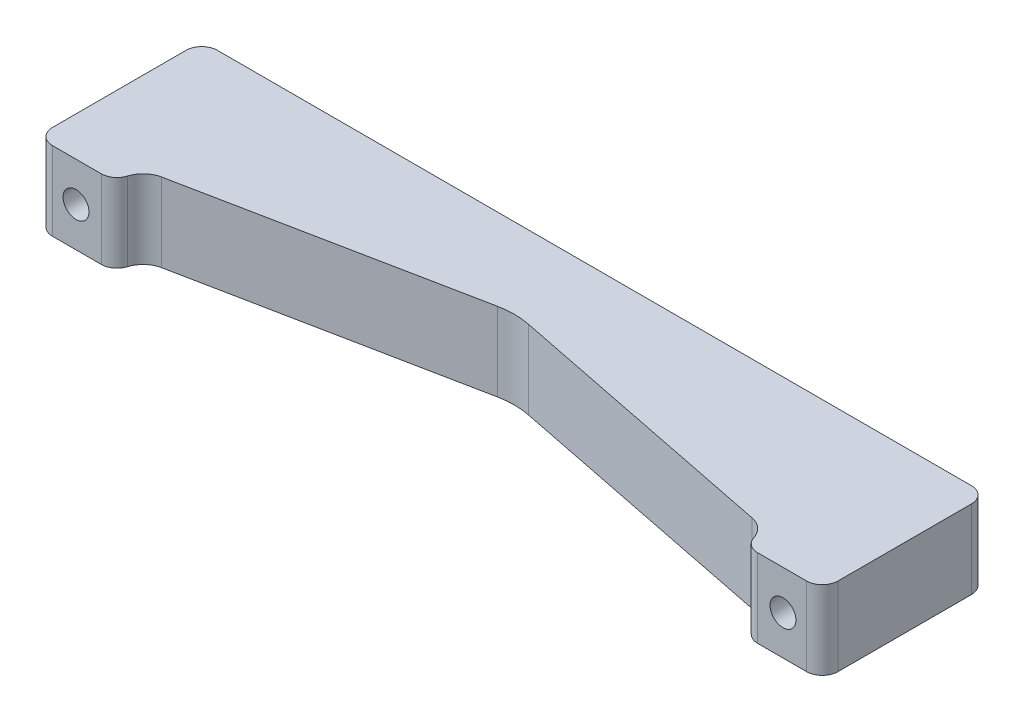
SolidWorks part; units mm, degrees
material "3.1355 (EN-AW 2024)"
ref_plane "Спереди" through (0, 0, 0) normal (0, 0, 1) x (1, 0, 0)
ref_plane "Сверху" through (0, 0, 0) normal (0, 1, 0) x (1, 0, 0)
ref_plane "Справа" through (0, 0, 0) normal (1, 0, 0) x (0, 0, -1)
sketch "Эскиз1" plane through (0, 0, 0) normal (0, 1, 0) x (1, 0, 0)
  line L0 (0, 0) -> (0, 11) construction
  line L1 (-30, 5) -> (30, 5) construction
  line L2 (-30, 5) -> (-30, -5) construction
  line L3 (-30, -5) -> (30, -5) construction
  line L4 (30, 5) -> (30, -5) construction
  line L5 (-30, 5) -> (30, -5) construction
  line L6 (-30, -5) -> (30, 5) construction
  line L7 (0, 11) -> (-40, 3)
  line L8 (-40, 3) -> (-40, 0)
  line L9 (-40, 0) -> (-50, 0)
  line L10 (0, 11) -> (0, 21) construction
  line L11 (50, 21) -> (-50, 21)
  line L12 (-50, 0) -> (-50, 21)
  line L13 (50, 0) -> (50, 21)
  line L14 (40, 0) -> (50, 0)
  line L15 (40, 3) -> (40, 0)
  line L16 (0, 11) -> (40, 3)
  point P0 (0, 0)
  dimension "D1" = 10
  dimension "D2" = 60
  dimension "D3" = 10
  dimension "D4" = 5
  dimension "D5" = 6
  dimension "D6" = 10
  dimension "D7" = 10
extrude "Бобышка-Вытянуть1" add sketch "Эскиз1" along normal blind 10
fillet "Скругление1" radius 3 2 edges at (40, 5, -3) (-40, 5, -3)
fillet "Скругление2" radius 10 1 edges at (0, 5, -11)
sketch "Эскиз2" plane through (0, 0, 0) normal (0, 0, 1) x (1, 0, 0)
  line L0 (-50, 5) -> (50, 5) construction
  line L1 (-50, 10) -> (-50, 0) construction
  line L2 (50, 10) -> (50, 0) construction
  line L3 (-45, 10) -> (-45, 0) construction
  line L4 (-50, 10) -> (-40, 10) construction
  line L5 (-50, 0) -> (-40, 0) construction
  line L6 (45, 10) -> (45, 0) construction
  line L7 (40, 10) -> (50, 10) construction
  line L8 (40, 0) -> (50, 0) construction
hole_wizard "Отверстие обработанное метчиком M4x0.71" positions "Эскиз4" profile "Эскиз3" tap size "M4x0.7" standard "Ansi Metric" end condition through all
sketch "Эскиз4" plane through (0, 0, 0) normal (0, 0, 1) x (1, 0, 0)
  line L0 (-50, 5) -> (50, 5) construction
  line L1 (-45, 10) -> (-45, 0) construction
  line L2 (45, 10) -> (45, 0) construction
  point P0 (-45, 5)
  point P2 (45, 5)
sketch "Эскиз3" plane through (-45, 5, 0) normal (1, 0, 0) x (0, -1, 0)
  line L0 (0, 0) -> (0, 21)
  line L1 (0, 21) -> (1.65, 21)
  line L2 (1.65, 21) -> (1.65, 0)
  line L5 (1.65, 0) -> (0, 0)
  line L11 (0, -6.35) -> (0, 107.95) construction
  dimension "Диаметр проходного сверла" = 3.3
  dimension "Глубина проходного сверла" = 21
cosmetic thread "Отверстие резьбы1" parameters "D2"=4
cosmetic thread "Отверстие резьбы2" parameters "D2"=4
fillet "Скругление3" radius 2 6 edges at (40, 5, 0) (50, 5, 0) (50, 5, -21) (-50, 5, -21) (-50, 5, 0) (-40, 5, 0)
sketch "Эскиз5" plane through (0, 0, 0) normal (0, 1, 0) x (1, 0, 0)
  line L0 (-50, 19) -> (-50, 2) construction
  line L1 (48, 21) -> (-48, 21) construction
  point P0 (-50, 21)
